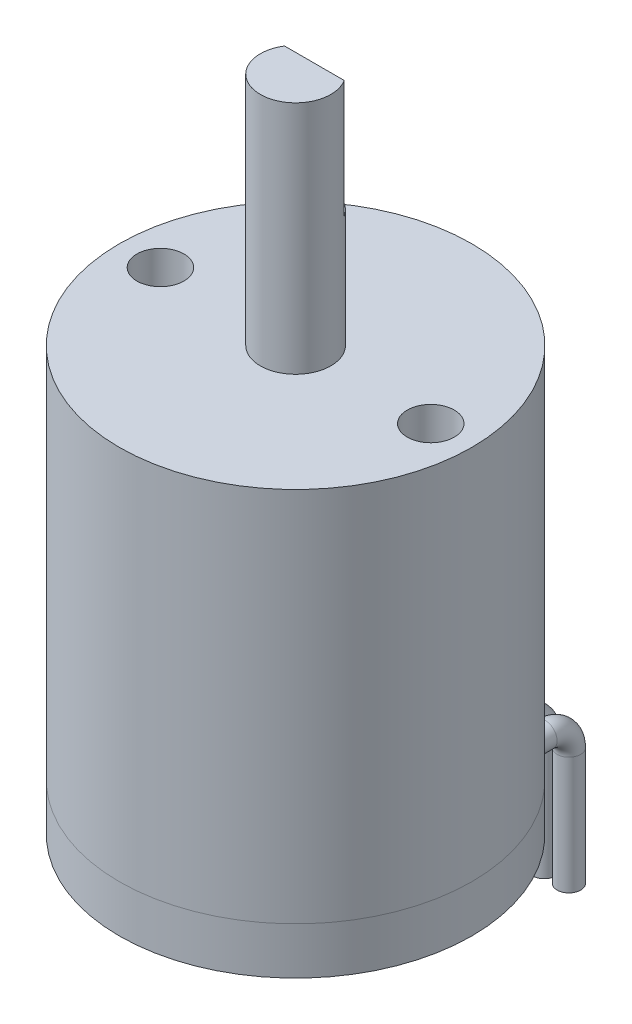
SolidWorks part; units mm, degrees
material "合金钢"
ref_plane "前视基准面" through (0, 0, 0) normal (0, 0, 1) x (1, 0, 0)
ref_plane "上视基准面" through (0, 0, 0) normal (0, 1, 0) x (1, 0, 0)
ref_plane "右视基准面" through (0, 0, 0) normal (1, 0, 0) x (0, 0, -1)
sketch "草图1" plane through (0, 0, 0) normal (0, 0, 1) x (1, 0, 0)
  line L0 (0, 0) -> (0, 28)
  line L1 (0, 28) -> (1.5, 28)
  line L2 (1.5, 28) -> (1.5, 18)
  line L3 (1.5, 18) -> (7.5, 18)
  line L4 (7.5, 18) -> (7.5, 0)
  line L5 (7.5, 0) -> (0, 0)
  dimension "D1" = 1.5
  dimension "D2" = 7.5
  dimension "D3" = 18
  dimension "D4" = 10
revolve "旋转1" add sketch "草图1" angle 360 about L0
sketch "草图2" plane through (0, 18, 0) normal (0, 1, 0) x (1, 0, 0)
  line L0 (-8.8159, 0) -> (8.6647, 0) construction
  line L1 (0, 0) -> (0, 8.6647) construction
  circle A0 centre (-5.75, 0) radius 1
  circle A1 centre (5.75, 0) radius 1
  dimension "D1" = 2
  dimension "D2" = 11.5
extrude "切除-拉伸1" cut sketch "草图2" against normal blind 5
sketch "草图3" plane through (0, 28, 0) normal (0, 1, 0) x (1, 0, 0)
  line L0 (0, 0) -> (0, 8.0651) construction
  line L1 (-2.5144, 5.1849) -> (2.5144, 5.1849)
  line L2 (-2.5144, 5.1849) -> (-2.5144, 0.8)
  line L3 (-2.5144, 0.8) -> (2.5144, 0.8)
  line L4 (2.5144, 5.1849) -> (2.5144, 0.8)
  line L5 (-2.5144, 5.1849) -> (2.5144, 0.8) construction
  line L6 (-2.5144, 0.8) -> (2.5144, 5.1849) construction
  point P0 (0, 2.9924)
  dimension "D1" = 0.8
extrude "切除-拉伸2" cut sketch "草图3" against normal blind 5
ref_plane "基准面1" through (0, 2, 0) normal (0, -1, 0) x (-1, 0, 0)
sketch "草图4" plane through (0, 2, 0) normal (0, -1, 0) x (-1, 0, 0)
  circle A1 centre (0, 0) radius 8
  dimension "D1" = 16
split line "分割线7"
sketch "草图5" plane through (0, 0, 0) normal (0, 0, 1) x (1, 0, 0)
  line L0 (0, 0) -> (0, 1) construction
  line L1 (0, 1) -> (0.525, 1) construction
  line L2 (0.525, 1) -> (2.625, 1) construction
  circle A0 centre (0.525, 1) radius 0.5
  circle A1 centre (1.575, 1) radius 0.5
  circle A2 centre (2.625, 1) radius 0.5
  circle A3 centre (-2.625, 1) radius 0.5
  circle A4 centre (-1.575, 1) radius 0.5
  circle A5 centre (-0.525, 1) radius 0.5
  dimension "D2" = 1
  dimension "D5" = 1.05
  dimension "D1" = 1
  dimension "D4" = 2.1
  dimension "D3" = 3
sketch "草图6" plane through (0, 0, 0) normal (1, 0, 0) x (0, 0, -1)
  line L0 (0, 1) -> (8, 1)
  line L1 (0, 1.5) -> (0, 0.5) construction
  line L2 (9, 0) -> (9, -5)
  arc A0 (8, 1) -> (9, 0) centre (8, 0) cw
  dimension "D2" = 1
  dimension "D1" = 8
  dimension "D3" = 5
sweep "扫描2" add profiles "草图5" path "草图6"
